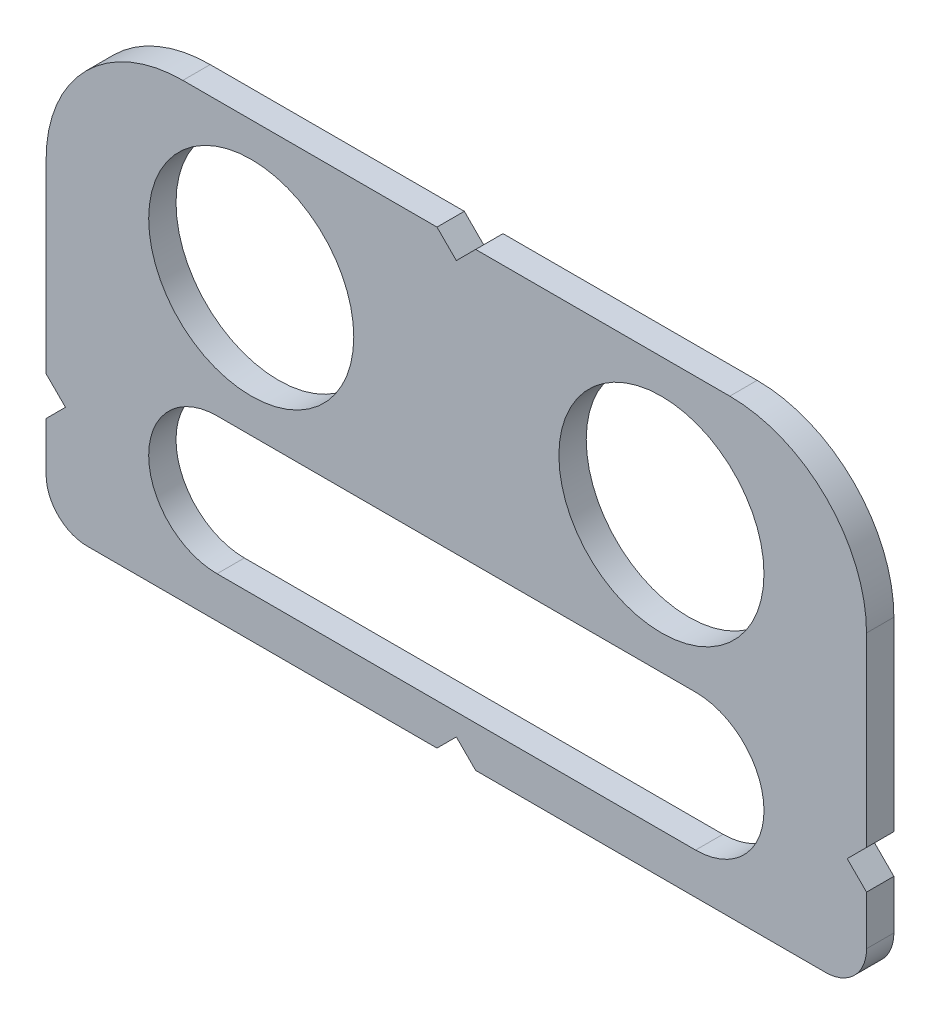
SolidWorks part; units mm, degrees
ref_plane "Front Plane" through (0, 0, 0) normal (0, 0, 1) x (1, 0, 0)
ref_plane "Top Plane" through (0, 0, 0) normal (0, 1, 0) x (1, 0, 0)
ref_plane "Right Plane" through (0, 0, 0) normal (1, 0, 0) x (0, 0, -1)
sketch "Sketch1" plane through (0, 0, 0) normal (0, 0, 1) x (1, 0, 0)
  line L0 (0, 49.2257) -> (0, 0) construction
  line L1 (0, 0) -> (57.1716, 0) construction
  line L2 (-17.5, 0) -> (17.5, 0) construction
  line L3 (-20, 25) -> (-1.4142, 25)
  line L4 (-30, 15) -> (-30, 1.4142)
  line L5 (-27, -8) -> (-1.4142, -8)
  line L6 (30, 15) -> (30, 1.4142)
  line L7 (-17.5, 5) -> (17.5, 5)
  line L8 (-17.5, -5) -> (17.5, -5)
  line L9 (30, 1.4142) -> (28.5858, 0)
  line L10 (28.5858, 0) -> (30, -1.4142)
  line L11 (30, -1.4142) -> (30, -5)
  line L12 (-30, 1.4142) -> (-28.5858, 0)
  line L13 (-28.5858, 0) -> (-30, -1.4142)
  line L14 (-30, -1.4142) -> (-30, -5)
  line L15 (-1.4142, 25) -> (0, 23.5858)
  line L16 (1.4142, 25) -> (0, 23.5858)
  line L17 (1.4142, 25) -> (20, 25)
  line L18 (0, -6.5858) -> (-1.4142, -8)
  line L19 (0, -6.5858) -> (1.4142, -8)
  line L20 (1.4142, -8) -> (27, -8)
  circle A0 centre (15, 15) radius 7.5
  circle A1 centre (-15, 15) radius 7.5
  arc A2 (-17.5, 5) -> (-17.5, -5) centre (-17.5, 0) ccw
  arc A3 (17.5, -5) -> (17.5, 5) centre (17.5, 0) ccw
  arc A4 (20, 25) -> (30, 15) centre (20, 15) cw
  arc A5 (-20, 25) -> (-30, 15) centre (-20, 15) ccw
  arc A6 (27, -8) -> (30, -5) centre (27, -5) ccw
  arc A7 (-30, -5) -> (-27, -8) centre (-27, -5) ccw
  point P14 (0, 0)
  point P25 (30, -8)
  point P28 (-30, -8)
  dimension "D4" = 30
  dimension "D6" = 15
  dimension "D7" = 10
  dimension "D8" = 3
  dimension "D1" = 60
  dimension "D2" = 25
  dimension "D3" = 8
  dimension "D5" = 15
  dimension "D9" = 35
  dimension "D10" = 45
  dimension "D11" = 2
  dimension "D12" = 10
  dimension "D13" = 90
  dimension "D14" = 2
  dimension "D15" = 90
  dimension "D16" = 2
extrude "Boss-Extrude1" add sketch "Sketch1" along normal blind 2
